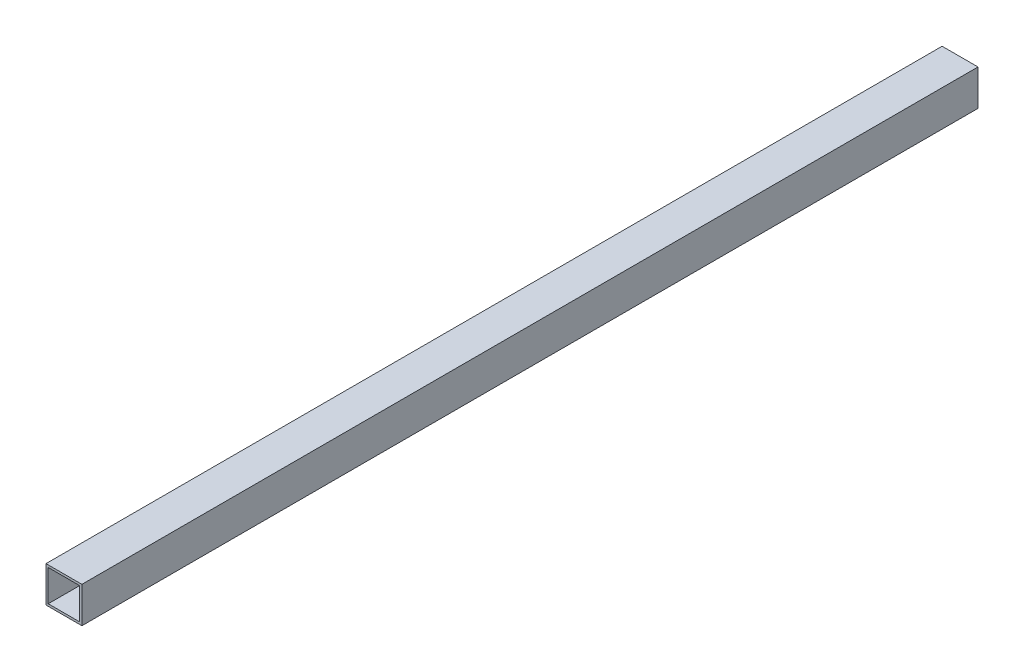
SolidWorks part; units mm, degrees
ref_plane "Alzado" through (0, 0, 0) normal (0, 0, 1) x (1, 0, 0)
ref_plane "Planta" through (0, 0, 0) normal (0, 1, 0) x (1, 0, 0)
ref_plane "Vista lateral" through (0, 0, 0) normal (1, 0, 0) x (0, 0, -1)
sketch "Croquis1" plane through (0, 0, 0) normal (0, 0, 1) x (1, 0, 0)
  line L0 (4.7625, -4.7625) -> (71.4375, -4.7625)
  line L1 (0, 0) -> (76.2, 0)
  line L2 (0, 0) -> (0, -76.2)
  line L3 (0, -76.2) -> (76.2, -76.2)
  line L4 (76.2, 0) -> (76.2, -76.2)
  line L5 (71.4375, -4.7625) -> (71.4375, -71.4375)
  line L6 (4.7625, -71.4375) -> (71.4375, -71.4375)
  line L7 (4.7625, -4.7625) -> (4.7625, -71.4375)
  dimension "D1" = 76.2
  dimension "D2" = 76.2
  dimension "D3" = 4.7625
extrude "Saliente-Extruir1" add sketch "Croquis1" along normal blind 1902.4
